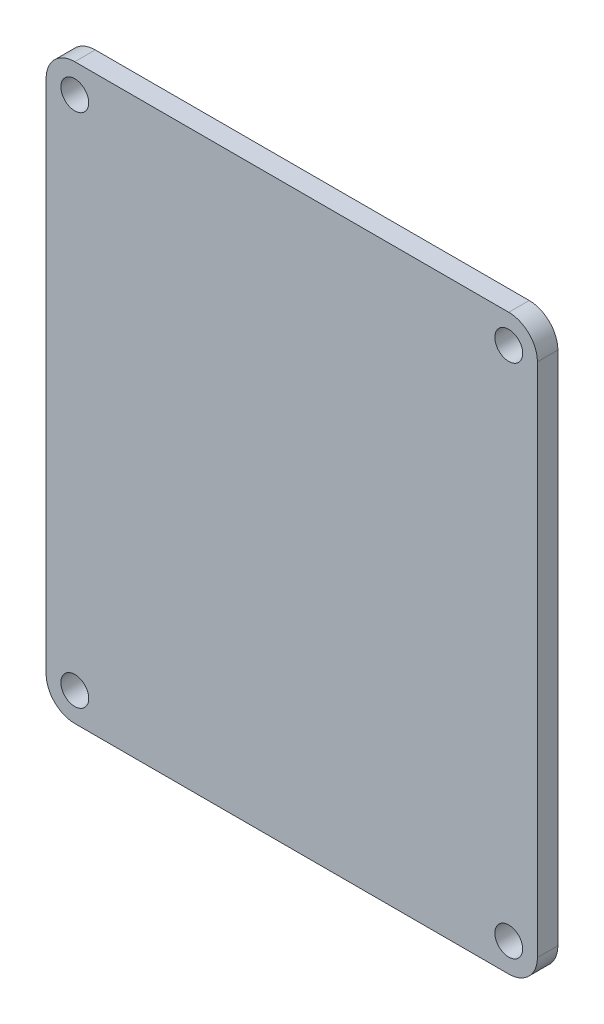
SolidWorks part; units mm, degrees
ref_plane "Front Plane" through (0, 0, 0) normal (1, 0, 0) x (0, 1, 0)
ref_plane "Top Plane" through (0, 0, 0) normal (0, 0, 1) x (0, 1, 0)
ref_plane "Right Plane" through (0, 0, 0) normal (0, 1, 0) x (-1, 0, 0)
sketch "Sketch1" plane through (0, 0, 0) normal (0, 0, 1) x (0, 1, 0)
  line L1 (-31.5, -30) -> (31.5, -30)
  line L2 (-35, -26.5) -> (-35, 26.5)
  line L3 (-31.5, 30) -> (31.5, 30)
  line L4 (35, -26.5) -> (35, 26.5)
  line L5 (-35, -30) -> (35, 30) construction
  line L6 (-35, 30) -> (35, -30) construction
  arc A0 (-35, 26.5) -> (-31.5, 30) centre (-31.5, 26.5) cw
  arc A1 (31.5, 30) -> (35, 26.5) centre (31.5, 26.5) cw
  arc A2 (31.5, -30) -> (35, -26.5) centre (31.5, -26.5) ccw
  arc A3 (-31.5, -30) -> (-35, -26.5) centre (-31.5, -26.5) cw
  circle A4 centre (-31.5, -26.5) radius 1.7
  circle A5 centre (-31.5, 26.5) radius 1.7
  circle A6 centre (31.5, 26.5) radius 1.7
  circle A7 centre (31.5, -26.5) radius 1.7
  point P0 (0, 0)
  dimension "D3" = 3.5
  dimension "D4" = 3.5
  dimension "D5" = 3.5
  dimension "D6" = 3.5
  dimension "D1" = 60
  dimension "D2" = 70
extrude "Boss-Extrude1" add sketch "Sketch1" along normal blind 2.5
